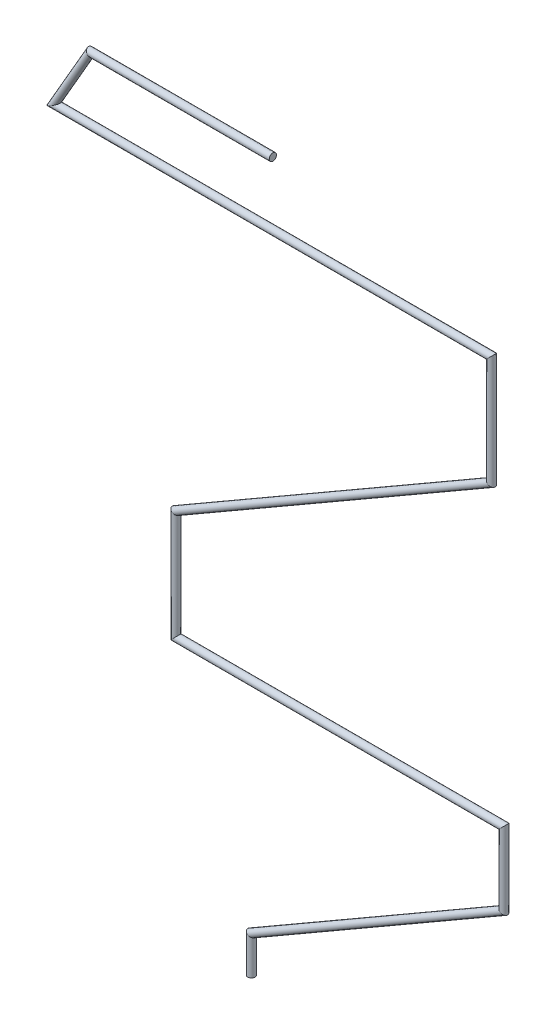
SolidWorks part; units mm, degrees
ref_plane "Piano frontale" through (0, 0, 0) normal (0, 0, 1) x (1, 0, 0)
ref_plane "Piano superiore" through (0, 0, 0) normal (0, 1, 0) x (1, 0, 0)
ref_plane "Piano destro" through (0, 0, 0) normal (1, 0, 0) x (0, 0, -1)
sketch "Schizzo39" plane through (0, 0, 0) normal (0, 0, 1) x (1, 0, 0)
  line L0 (0, 0) -> (0, 5)
  line L1 (0, 5) -> (34.641, 25)
  line L2 (34.641, 25) -> (34.641, 35)
  line L3 (34.641, 35) -> (-10.359, 35)
  line L4 (-10.359, 35) -> (-10.359, 50)
  line L5 (-10.359, 50) -> (32.9423, 75)
  line L6 (32.9423, 75) -> (32.9423, 90)
  line L7 (32.9423, 90) -> (-27.0577, 90)
  line L8 (-27.0577, 90) -> (-22.0577, 98.6603)
  line L9 (-22.0577, 98.6603) -> (2.9423, 98.6603)
  line L10 (2.9423, 98.6603) -> (2.9423, 103.6603)
  line L11 (2.9423, 103.6603) -> (7.9423, 113.6603)
  line L12 (7.9423, 113.6603) -> (7.9423, 123.6603)
  dimension "D1" = 5
  dimension "D2" = 40
  dimension "D3" = 20
  dimension "D4" = 10
  dimension "D5" = 45
  dimension "D6" = 15
  dimension "D7" = 50
  dimension "D8" = 25
  dimension "D9" = 15
  dimension "D10" = 60
  dimension "D11" = 10
  dimension "D12" = 5
  dimension "D13" = 25
  dimension "D14" = 5
  dimension "D15" = 10
  dimension "D16" = 5
  dimension "D17" = 10
sweep "Sweep1" add path "Schizzo39" circular profile diameter 1 parameters "D3"=1
